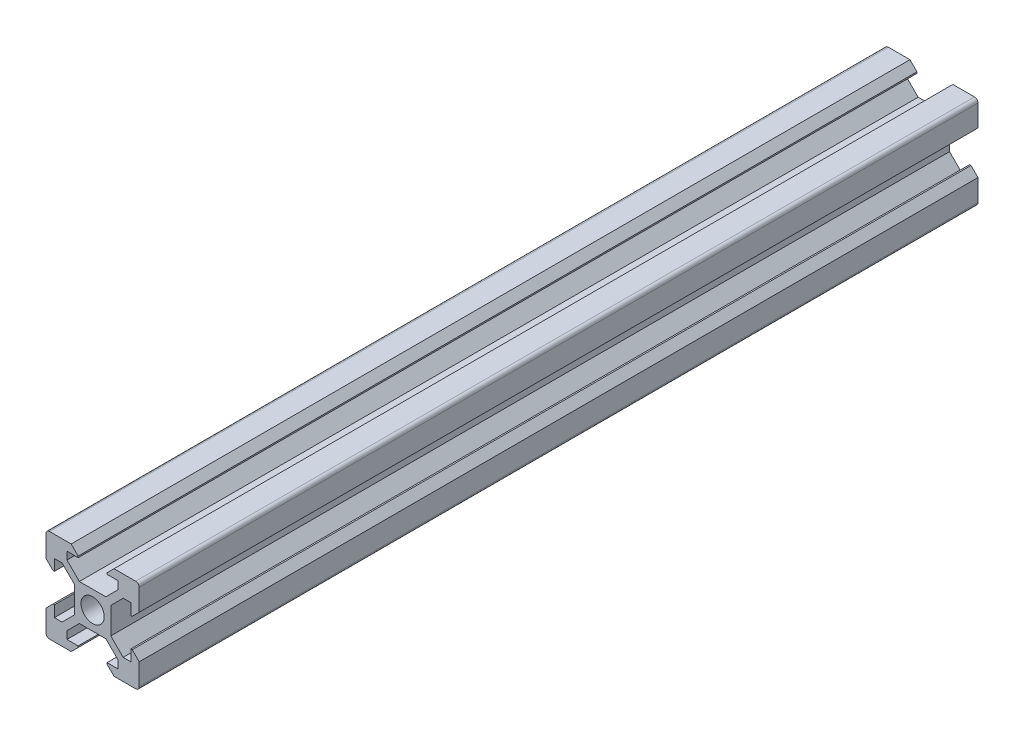
SolidWorks part; units mm, degrees
other "Markup1"
sketch "Sketch1" plane through (10, 10, 480) normal (0.5774, 0.5773, 0.5774) x (0.7071, 0, -0.7071)
ref_plane "Alzado" through (0, 0, 0) normal (0, 0, 1) x (1, 0, 0)
ref_plane "Planta" through (0, 0, 0) normal (0, 1, 0) x (1, 0, 0)
ref_plane "Vista lateral" through (0, 0, 0) normal (1, 0, 0) x (0, 0, -1)
sketch "Croquis1" plane through (0, 0, 0) normal (0, 0, 1) x (1, 0, 0)
  line L0 (-4.6, 10) -> (-3.1, 8.5)
  line L3 (-4.6, 10) -> (-9.25, 10)
  line L5 (-3.1, 8.5) -> (-3.1, 8.2)
  line L6 (-3.1, 8.2) -> (-5.5, 8.2)
  line L7 (-5.5, 8.2) -> (-5.5, 6.5607)
  line L8 (-5.5, 6.5607) -> (-2.84, 3.9007)
  line L9 (-2.84, 3.9007) -> (0, 3.9007)
  line L10 (0, 0) -> (-15.3499, 15.3499) construction
  line L11 (-3.9007, 2.84) -> (-3.9007, 0)
  line L12 (-6.5607, 5.5) -> (-3.9007, 2.84)
  line L13 (-8.2, 5.5) -> (-6.5607, 5.5)
  line L14 (-8.2, 3.1) -> (-8.2, 5.5)
  line L15 (-8.5, 3.1) -> (-8.2, 3.1)
  line L16 (-10, 4.6) -> (-10, 9.25)
  line L17 (-10, 4.6) -> (-8.5, 3.1)
  line L18 (10, 4.6) -> (8.5, 3.1)
  line L19 (10, 4.6) -> (10, 9.25)
  line L20 (8.5, 3.1) -> (8.2, 3.1)
  line L21 (8.2, 3.1) -> (8.2, 5.5)
  line L22 (8.2, 5.5) -> (6.5607, 5.5)
  line L23 (6.5607, 5.5) -> (3.9007, 2.84)
  line L24 (3.9007, 2.84) -> (3.9007, 0)
  line L25 (5.5, 6.5607) -> (2.84, 3.9007)
  line L26 (5.5, 8.2) -> (5.5, 6.5607)
  line L27 (3.1, 8.2) -> (5.5, 8.2)
  line L28 (3.1, 8.5) -> (3.1, 8.2)
  line L29 (4.6, 10) -> (9.25, 10)
  line L30 (4.6, 10) -> (3.1, 8.5)
  line L31 (2.84, 3.9007) -> (0, 3.9007)
  line L32 (4.6, -10) -> (3.1, -8.5)
  line L33 (4.6, -10) -> (9.25, -10)
  line L34 (3.1, -8.5) -> (3.1, -8.2)
  line L35 (3.1, -8.2) -> (5.5, -8.2)
  line L36 (5.5, -8.2) -> (5.5, -6.5607)
  line L37 (5.5, -6.5607) -> (2.84, -3.9007)
  line L38 (2.84, -3.9007) -> (0, -3.9007)
  line L39 (6.5607, -5.5) -> (3.9007, -2.84)
  line L40 (8.2, -5.5) -> (6.5607, -5.5)
  line L41 (8.2, -3.1) -> (8.2, -5.5)
  line L42 (8.5, -3.1) -> (8.2, -3.1)
  line L43 (10, -4.6) -> (10, -9.25)
  line L44 (10, -4.6) -> (8.5, -3.1)
  line L45 (3.9007, -2.84) -> (3.9007, 0)
  line L46 (-10, -4.6) -> (-8.5, -3.1)
  line L47 (-10, -4.6) -> (-10, -9.25)
  line L48 (-8.5, -3.1) -> (-8.2, -3.1)
  line L49 (-8.2, -3.1) -> (-8.2, -5.5)
  line L50 (-8.2, -5.5) -> (-6.5607, -5.5)
  line L51 (-6.5607, -5.5) -> (-3.9007, -2.84)
  line L52 (-3.9007, -2.84) -> (-3.9007, 0)
  line L53 (-5.5, -6.5607) -> (-2.84, -3.9007)
  line L54 (-5.5, -8.2) -> (-5.5, -6.5607)
  line L55 (-3.1, -8.2) -> (-5.5, -8.2)
  line L56 (-3.1, -8.5) -> (-3.1, -8.2)
  line L57 (-4.6, -10) -> (-9.25, -10)
  line L58 (-4.6, -10) -> (-3.1, -8.5)
  line L59 (-2.84, -3.9007) -> (0, -3.9007)
  circle A0 centre (0, 0) radius 2.5
  arc A1 (-9.25, 10) -> (-10, 9.25) centre (-9.25, 9.25) ccw
  arc A2 (10, 9.25) -> (9.25, 10) centre (9.25, 9.25) ccw
  arc A3 (9.25, -10) -> (10, -9.25) centre (9.25, -9.25) ccw
  arc A4 (-10, -9.25) -> (-9.25, -10) centre (-9.25, -9.25) ccw
  point P18 (-10, 10)
  point P37 (10, 10)
  point P55 (10, -10)
  point P73 (-10, -10)
  point P79 (0, 0)
  dimension "D1" = 5
  dimension "D5" = 0.75
  dimension "D2" = 10
  dimension "D3" = 10
  dimension "D4" = 4.6
  dimension "D6" = 5.5
  dimension "D7" = 135
  dimension "D8" = 0.75
  dimension "D9" = 225
  dimension "D10" = 2.84
  dimension "D11" = 1.8
  dimension "D12" = 3.1
  dimension "D13" = 4
extrude "Saliente-Extruir1" add sketch "Croquis1" along normal blind 480
sketch "Sketch2" plane through (0, 0, 0) normal (1, 0, 0) x (0, 0, -1)
  line L0 (-300, 40.7698) -> (-300, -37.1573) construction
  line L1 (-300, -13.485) -> (300, -13.485)
  line L2 (-300, -13.485) -> (-300, 13.485)
  line L3 (-300, 13.485) -> (300, 13.485)
  line L4 (300, -13.485) -> (300, 13.485)
  line L5 (-300, -13.485) -> (300, 13.485) construction
  line L6 (-300, 13.485) -> (300, -13.485) construction
  line L7 (-480, -2.84) -> (-480, 2.84) construction
  point P0 (0, 0)
  dimension "D1" = 180
extrude "Cut-Extrude1" cut sketch "Sketch2" against normal blind 24 and the other way blind 25 contours L2 L1 L4 L3
